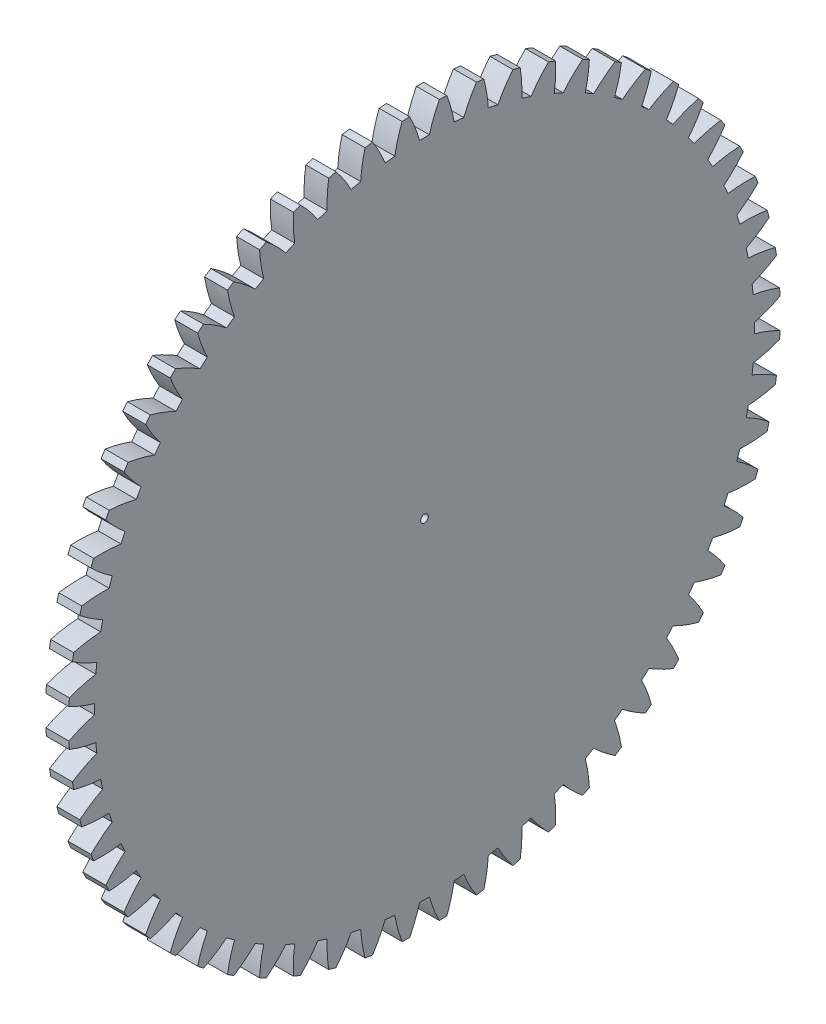
SolidWorks part; units mm, degrees
ref_plane "Plane1" through (0, 0, 0) normal (0, 0, 1) x (1, 0, 0)
ref_plane "Plane2" through (0, 0, 0) normal (0, 1, 0) x (1, 0, 0)
ref_plane "Plane3" through (0, 0, 0) normal (1, 0, 0) x (0, 0, -1)
sketch "HoldingSke" plane through (0, 0, 0) normal (0, 1, 0) x (1, 0, 0)
  line L0 (0, 0) -> (0.3333, -0.5774)
  line L1 (-15, 0) -> (100, 0) construction
  line L2 (0, 0) -> (-2.1039, 2.3779)
  line L3 (0, 0) -> (-11.863, 4.5341)
  line L4 (0, 0) -> (4.318, 7.479)
  line L5 (0, 0) -> (-46.8476, -17.4728)
  line L6 (0, 0) -> (-2.4869, -1.6779)
  line L7 (-2.1039, 2.3779) -> (8.6586, 51.2059)
  line L8 (-76.2, 54.61) -> (-76.1, 54.61)
  line L9 (-71.009, 38.7566) -> (-53.1078, 45.2721)
  line L10 (-76.2, 71.12) -> (104.1128, 71.12)
  line L11 (0, 0) -> (-3, 0)
  line L12 (-76.2, 101.6) -> (-76.147, 101.6)
  line L13 (24.9733, 27.94) -> (52.9518, 28.4284)
  line L14 (24.9733, 27.94) -> (24.9743, 27.94)
  line L15 (24.9733, 27.94) -> (100.4006, 29.5858)
  line L16 (-63.627, -1.5) -> (-12.827, -1.5)
  circle A0 centre (0, 0) radius 0.5
  circle A1 centre (0, 0) radius 37.5
  circle A2 centre (0, 0) radius 37.5
  circle A3 centre (0, 0) radius 0.5
  dimension "MHD" = 75
  dimension "Hub_dia" = 75
  dimension "Bore" = 1
  dimension "MBD" = 1
  dimension "Num_teeth" = 60
  dimension "Pitch" = 0.6667
  dimension "Overall_len" = 50
  dimension "Show_teeth" = 60
  dimension "Thickness" = 3
  dimension "OAL" = 50.0001
  dimension "T_dim" = 0.1
  dimension "Ap" = 20
  dimension "H" = 19.05
  dimension "Pitch_radius" = 180.3128
  dimension "Width" = 3
  dimension "Backlash" = 0.053
  dimension "Addendum_fac" = 1
  dimension "Dedendum_fac" = 1.25
  dimension "Clearance_fac" = 0.25
  dimension "Dedendum_add" = 0.001
  dimension "Module" = 1.5
sketch "BasProSke" plane through (0, 0, 0) normal (0, 1, 0) x (1, 0, 0)
  line L0 (-10, 0) -> (60, 0) construction
  line L1 (0, 0) -> (0, 46.5)
  line L2 (0, 0) -> (3, 0)
  line L3 (3, 0) -> (3, 46.5)
  line L4 (3, 46.5) -> (0, 46.5)
  dimension "Thickness" = 3
  dimension "Diameter" = 93
revolve "Base-Revolve" add sketch "BasProSke" angle 360 about L0
sketch "TooCutSke" plane through (0, 0, 0) normal (1, 0, 0) x (0, 0, -1)
  line L1 (0, 0) -> (0, 107) construction
  line L2 (0, 0) -> (-1.2707, 44.9821) construction
  line L3 (0, 0) -> (-4.7089, 89.8505) construction
  line L4 (-1.2707, 44.9821) -> (-2.3544, 44.9253) construction
  arc A0 (0.6387, 43.1193) -> (-0.6387, 43.1193) centre (0, 0) ccw
  arc A1 (1.9554, 46.4843) -> (-1.9554, 46.4843) centre (0, 0) ccw
  circle A2 centre (0, 0) radius 45 construction
  circle A3 centre (0, 0) radius 42.2862 construction
  arc A4 (-0.6387, 43.1193) -> (-1.9554, 46.4843) centre (-17.9747, 38.2757) ccw
  arc A5 (1.9554, 46.4843) -> (0.6387, 43.1193) centre (17.9747, 38.2757) ccw
  dimension "Root_dia" = 86.248
  dimension "Overcut_dia" = 93.0508
  dimension "Pitch_dia" = 90
  dimension "Base_dia" = 84.5723
  dimension "Flank_rad" = 18
  dimension "Half_ang" = 3
  dimension "Half_CT" = 1.0852
extrude "ToothCut" cut sketch "TooCutSke" along normal through all
fillet "Breaks" [suppressed] radius 0.03
fillet "RootFillets" [suppressed] radius 0.376
pattern_circular "TeethCuts" count 60 every 6 about axis through (-10, 0, 0) along (1, 0, 0) of "ToothCut", "RootFillets", "Breaks"
sketch "HubNeaOneSke" plane through (0, 0, 0) normal (-1, 0, 0) x (0, 0, 1)
  circle A0 centre (0, 0) radius 37.5
  dimension "Diameter" = 75
extrude "HubNearOne" [suppressed] add sketch "HubNeaOneSke" along normal blind 47.0001
sketch "HubNeaBotSke" plane through (0, 0, 0) normal (-1, 0, 0) x (0, 0, 1)
  circle A0 centre (0, 0) radius 37.5
  dimension "Diameter" = 75
extrude "HubNearBoth" [suppressed] add sketch "HubNeaBotSke" along normal blind 23.5
ref_plane "FarPln" through (3, 0, 0) normal (1, 0, 0) x (0, 0, -1)
sketch "HubFarSke" plane through (3, 0, 0) normal (1, 0, 0) x (0, 0, -1)
  circle A0 centre (0, 0) radius 37.5
  dimension "Diameter" = 75
extrude "HubFar" [suppressed] add sketch "HubFarSke" along normal blind 23.5
sketch "BorSke" plane through (0, 0, 0) normal (1, 0, 0) x (0, 0, -1)
  circle A0 centre (0, 0) radius 0.5
  dimension "Diameter" = 1
extrude "Bore" cut sketch "BorSke" along normal mid plane 100.0001
sketch "KeySke" plane through (0, 0, 0) normal (1, 0, 0) x (0, 0, -1)
  line L0 (-0.05, 0) -> (-0.05, 0.6)
  line L1 (-0.05, 0.6) -> (0.05, 0.6)
  line L2 (0.05, 0.6) -> (0.05, 0)
  line L3 (0, 0) -> (0, 34) construction
  line L4 (-0.05, 0) -> (0.05, 0)
  dimension "Offset" = 0.6
  dimension "Width" = 0.1
extrude "Keyway" [suppressed] cut sketch "KeySke" along normal mid plane 100.0001
pattern_circular "Keyway2" [suppressed] count 2 every 90 about axis through (-10, 0, 0) along (1, 0, 0)
equation "' \"Module@HoldingSke\" = 6.35"
equation "' \"Num_teeth@HoldingSke\" = 12"
equation "' \"Ap@HoldingSke\" =  20"
equation "' \"Ap@HoldingSke\" = 20"
equation "' \"Width@HoldingSke\" = 0.5 * 25.4"
equation "' \"Hub_dia@HoldingSke\"= 1 * 25.4"
equation "' \"Hub_dia@HoldingSke\" = 1 * 25.4"
equation "' \"Overall_len@HoldingSke\" = 1.0 * 25.4"
equation "' \"Bore@HoldingSke\" = 0.75 * 25.4"
equation "' \"T_dim@HoldingSke\" = 0.1 * 25.4"
equation "' \"Width@KeySke\" = 0.25 * 25.4"
equation "' \"Show_teeth@HoldingSke\" = 13"
equation "' \"Backlash@HoldingSke\" = 0.009 * 25.4"
equation "' \"Addendum_fac@HoldingSke\" = 1.0"
equation "' \"Dedendum_fac@HoldingSke\" = 1.25"
equation "' \"Dedendum_add@HoldingSke\" = 0.00005 * 25.4"
equation "' \"Clearance_fac@HoldingSke\" = 0.25"
equation "\"Pitch@HoldingSke\" = 1 / \"Module@HoldingSke\""
equation "\"Overcut_dia@TooCutSke\" = (\"Num_teeth@HoldingSke\" + 2 * \"Addendum_fac@HoldingSke\") / \"Pitch@HoldingSke\" + 0.002 * 25.4"
equation "\"Pitch_dia@TooCutSke\" = \"Num_teeth@HoldingSke\" / \"Pitch@HoldingSke\""
equation "\"Base_dia@TooCutSke\" = \"Num_teeth@HoldingSke\" / \"Pitch@HoldingSke\" * cos((\"Ap@HoldingSke\"  * 3.14159265 / 180))"
equation "\"Root_dia@TooCutSke\" = (\"Num_teeth@HoldingSke\" + 2) / \"Pitch@HoldingSke\" - 2 * (\"Addendum_fac@HoldingSke\" + \"Dedendum_fac@HoldingSke\") / \"Pitch@HoldingSke\" - \"Dedendum_add@HoldingSke\" * 2"
equation "\"Half_ang@TooCutSke\" = 180 / \"Num_teeth@HoldingSke\""
equation "\"Half_CT@TooCutSke\" = \"Num_teeth@HoldingSke\" / \"Pitch@HoldingSke\" * sin((3.14159265 / 2 / \"Num_teeth@HoldingSke\")) / 2 - 7 * \"Backlash@HoldingSke\" / 4"
equation "\"Flank_rad@TooCutSke\" = \"Num_teeth@HoldingSke\" / \"Pitch@HoldingSke\" / 5"
equation "\"Radius@RootFillets\" = \"Clearance_fac@HoldingSke\" / \"Pitch@HoldingSke\" + \"Dedendum_add@HoldingSke\""
equation "\"Break_rad@Breaks\" = 0.02 / \"Pitch@HoldingSke\""
equation "\"Thickness@HoldingSke\" = \"Width@HoldingSke\""
equation "\"OAL@HoldingSke\" = \"Thickness@HoldingSke\""
equation "\"MHD@HoldingSke\" = (\"Num_teeth@HoldingSke\" + 2) / \"Pitch@HoldingSke\" - 2 * (\"Addendum_fac@HoldingSke\" + \"Dedendum_fac@HoldingSke\")  / \"Pitch@HoldingSke\" - \"Dedendum_add@HoldingSke\" * 2"
equation "\"MBD@HoldingSke\" = (\"Num_teeth@HoldingSke\" + 2) / \"Pitch@HoldingSke\" - 2 * (\"Addendum_fac@HoldingSke\" + \"Dedendum_fac@HoldingSke\")  / \"Pitch@HoldingSke\" - \"Dedendum_add@HoldingSke\" * 2 - 0.002 * 25.4"
equation "\"MHD@HoldingSke\" = ((sgn( \"MHD@HoldingSke\" - \"Hub_dia@HoldingSke\" )-1)*( \"MHD@HoldingSke\" - \"Hub_dia@HoldingSke\" ))/-2+ \"Hub_dia@HoldingSke\""
equation "\"MBD@HoldingSke\" = ((sgn( \"MBD@HoldingSke\" - \"Bore@HoldingSke\" )-1)*( \"MBD@HoldingSke\" - \"Bore@HoldingSke\" ))/-2+ \"Bore@HoldingSke\""
equation "\"OAL@HoldingSke\" = ((sgn( \"OAL@HoldingSke\" - \"Overall_len@HoldingSke\" )+1)*( \"OAL@HoldingSke\" - \"Overall_len@HoldingSke\" ))/2 + \"Overall_len@HoldingSke\" + 0.000002 * 25.4"
equation "\"Num_teeth@TeethCuts\" = int( \"Show_teeth@HoldingSke\" ) + 1"
equation "\"Num_teeth@TeethCuts\" = ((sgn( \"Num_teeth@TeethCuts\" - \"Num_teeth@HoldingSke\" )-1)*( \"Num_teeth@TeethCuts\" - \"Num_teeth@HoldingSke\" ))/-2+ \"Num_teeth@HoldingSke\""
equation "\"Num_teeth@TeethCuts\" = ((sgn( \"Num_teeth@TeethCuts\" - 2.0)+1)*( \"Num_teeth@TeethCuts\" - 2.0))/2 +2.0"
equation "\"Angle@TeethCuts\" = 360.0 / \"Num_teeth@HoldingSke\""
equation "\"Diameter@BasProSke\" = (\"Num_teeth@HoldingSke\" + 2 * \"Addendum_fac@HoldingSke\") / \"Pitch@HoldingSke\""
equation "\"Thickness@BasProSke\"  = \"Thickness@HoldingSke\""
equation "' \"Fillet_rad@BasProSke\" =  \"Thickness@HoldingSke\" * 0.05"
equation "' \"Fillet_rad@BasProSke\" = \"Thickness@HoldingSke\" * 0.05"
equation "\"MHD@HoldingSke\" = ((sgn( \"MHD@HoldingSke\" - \"Root_dia@TooCutSke\" )-1)*( \"MHD@HoldingSke\" - \"Root_dia@TooCutSke\" ))/-2+ \"Root_dia@TooCutSke\""
equation "\"Diameter@HubNeaOneSke\" = \"MHD@HoldingSke\""
equation "\"Length@HubNearOne\" = \"OAL@HoldingSke\" - \"Thickness@BasProSke\""
equation "\"Diameter@HubNeaBotSke\" = \"MHD@HoldingSke\""
equation "\"Length@HubNearBoth\" = ( \"OAL@HoldingSke\" - \"Thickness@BasProSke\" ) / 2.0"
equation "\"Thickness@FarPln\" = \"Thickness@BasProSke\""
equation "\"Diameter@HubFarSke\" = \"MHD@HoldingSke\""
equation "\"Length@HubFar\" = ( \"OAL@HoldingSke\" - \"Thickness@BasProSke\" ) / 2.0"
equation "\"Diameter@BorSke\" = \"MBD@HoldingSke\""
equation "\"D1@Bore\" = \"OAL@HoldingSke\" * 2.0"
equation "\"D1@Keyway\" = \"OAL@HoldingSke\" * 2.0"
equation "\"Offset@KeySke\" = \"T_dim@HoldingSke\" + \"MBD@HoldingSke\" / 2.0"
